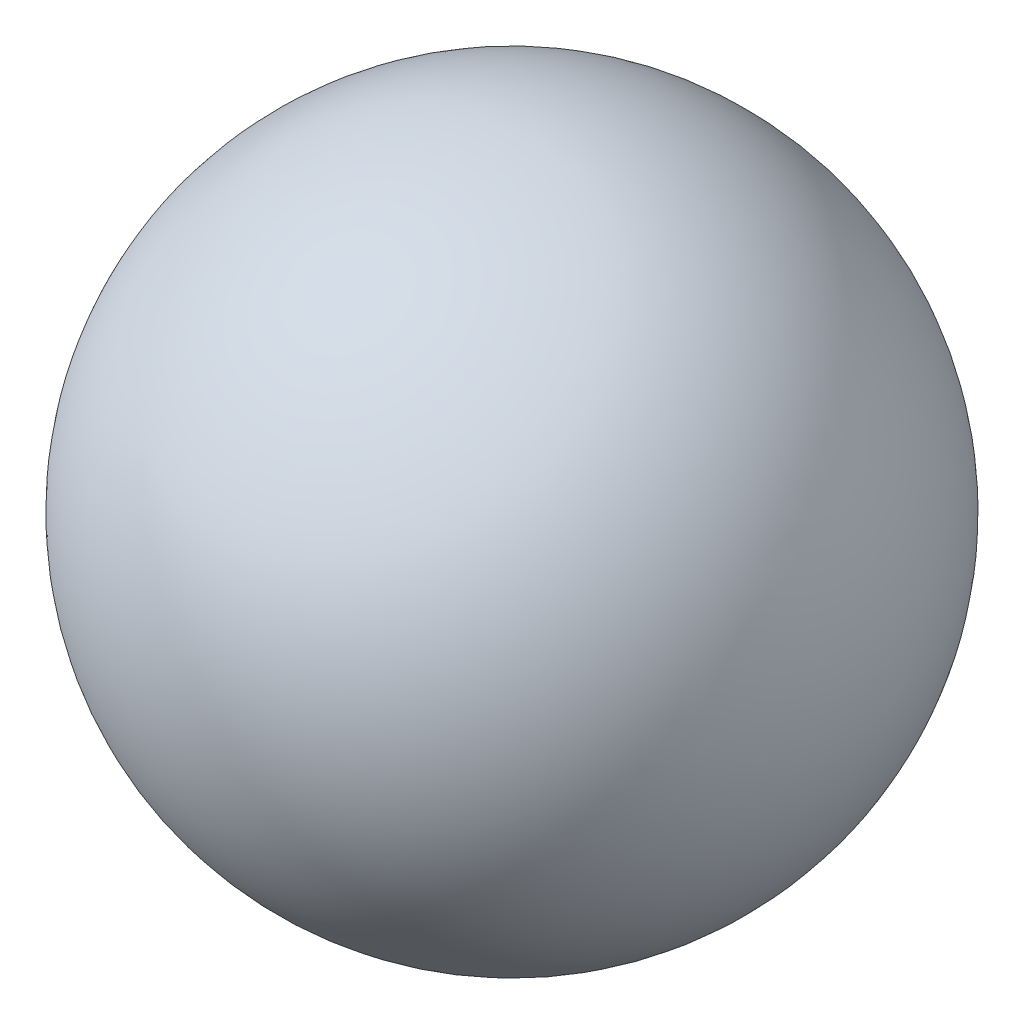
SolidWorks part; units mm, degrees
ref_plane "Plan de face" through (0, 0, 0) normal (0, 0, 1) x (1, 0, 0)
ref_plane "Plan de dessus" through (0, 0, 0) normal (0, 1, 0) x (1, 0, 0)
ref_plane "Plan de droite" through (0, 0, 0) normal (1, 0, 0) x (0, 0, -1)
sketch "Esquisse1" plane through (0, 0, 0) normal (0, 0, 1) x (1, 0, 0)
  line L0 (-21.5, 0) -> (21.5, 0)
  arc A0 (-21.5, 0) -> (21.5, 0) centre (0, 0) cw
  point P4 (0, 0)
  dimension "D1" = 43
revolve "Révolution1" add sketch "Esquisse1" angle 360 about L0
